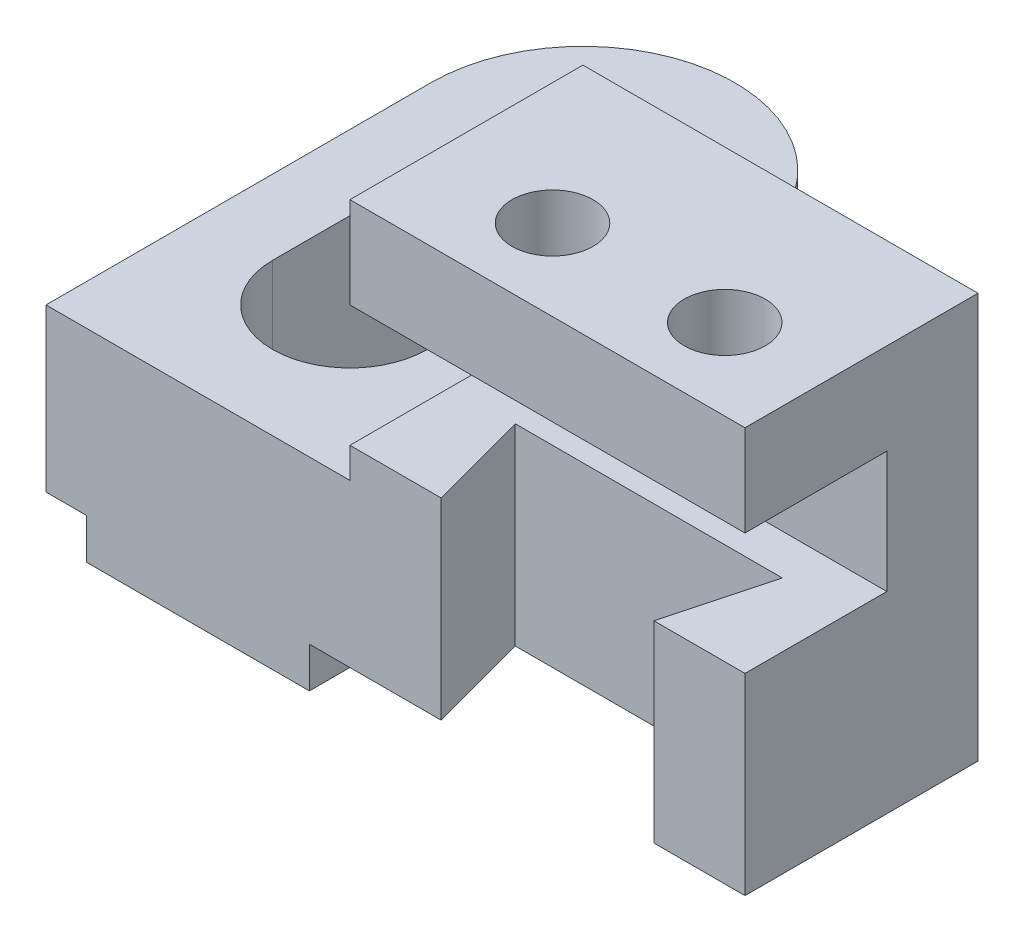
SolidWorks part; units mm, degrees
ref_plane "Front Plane" through (0, 0, 0) normal (0, 0, 1) x (1, 0, 0)
ref_plane "Top Plane" through (0, 0, 0) normal (0, 1, 0) x (1, 0, 0)
ref_plane "Right Plane" through (0, 0, 0) normal (1, 0, 0) x (0, 0, -1)
sketch "Sketch2" plane through (0, 0, 0) normal (0, 1, 0) x (1, 0, 0)
  line L0 (0, 43.411) -> (0, 20.411) construction
  line L1 (-15, 5.411) -> (15, 5.411)
  line L2 (-15, 5.411) -> (-15, 43.411)
  line L3 (-15, 43.411) -> (15, 43.411)
  line L4 (15, 5.411) -> (15, 43.411)
  line L7 (7.6308, 43.411) -> (7.6308, 20.411)
  line L8 (-7.6308, 43.411) -> (-7.6308, 20.411)
  arc A2 (-15, 43.411) -> (15, 43.411) centre (0, 43.411) cw
  arc A3 (7.6308, 43.411) -> (-7.6308, 43.411) centre (0, 43.411) ccw
  arc A4 (-7.6308, 20.411) -> (7.6308, 20.411) centre (0, 20.411) ccw
  point P4 (0, 31.911)
  point P13 (-15, 24.411)
  dimension "D4" = 15
  dimension "D1" = 38
  dimension "D2" = 23
extrude "Boss-Extrude1" add sketch "Sketch2" against normal blind 16 contours A4 L8 L3 L2 L1 L4 L7 | A3 L3 A2
sketch "Sketch4" plane through (15, 0, 0) normal (1, 0, 0) x (0, 0, -1)
  line L1 (5.411, 0) -> (43.411, 0) construction
  line L3 (5.411, 24) -> (5.411, 15)
  line L4 (5.411, 15) -> (19.411, 15)
  line L5 (19.411, 15) -> (19.411, 3)
  line L6 (19.411, 3) -> (5.411, 3)
  line L7 (5.411, 3) -> (5.411, 0)
  line L8 (5.411, -16) -> (5.411, 0) construction
  line L10 (5.411, 24) -> (28.411, 24)
  line L11 (28.411, 24) -> (28.411, 0)
  line L12 (28.411, 0) -> (5.411, 0)
  dimension "D1" = 9
  dimension "D2" = 40
  dimension "D3" = 23
  dimension "D4" = 19
  dimension "D5" = 9
extrude "Boss-Extrude2" add sketch "Sketch4" along normal blind 39 separate body
sketch "Sketch5" plane through (0, 24, 0) normal (0, 1, 0) x (1, 0, 0)
  line L0 (15, 5.411) -> (15, 28.411) construction
  line L1 (54, 5.411) -> (15, 5.411) construction
  circle A0 centre (27, 13.411) radius 4
  circle A1 centre (44, 13.411) radius 4
  dimension "D1" = 8
  dimension "D2" = 8
  dimension "D3" = 12
  dimension "D4" = 17
  dimension "D5" = 8
  dimension "D6" = 8
extrude "Cut-Extrude1" cut sketch "Sketch5" against normal blind 9
sketch "Sketch7" plane through (0, 0, -5.411) normal (0, 0, 1) x (1, 0, 0)
  line L0 (15, 0) -> (54, 0)
  line L1 (54, 0) -> (54, -16)
  line L2 (54, -16) -> (15, -16)
  line L3 (15, -16) -> (15, 0)
extrude "Boss-Extrude3" add sketch "Sketch7" against normal blind 23
sketch "Sketch9" plane through (0, 3, 0) normal (0, 1, 0) x (1, 0, 0)
  line L0 (15, 5.411) -> (24, 5.411)
  line L1 (54, 5.411) -> (15, 5.411) construction
  line L2 (24, 5.411) -> (21.3205, 15.411)
  line L3 (15, 15.411) -> (54, 15.411)
  line L4 (21.3205, 15.411) -> (47.6795, 15.411)
  line L5 (45, 5.411) -> (54, 5.411)
  line L6 (54, 5.411) -> (54, 13.4741)
  line L7 (54, 28.411) -> (54, 5.411) construction
  line L8 (54, 15.411) -> (54, 13.4741)
  line L9 (15, 5.411) -> (15, 28.411) construction
  line L10 (15, 13.4741) -> (15, 5.411)
  line L11 (15, 5.411) -> (24, 5.411)
  line L12 (15, 5.411) -> (54, 5.411)
  line L13 (47.6795, 15.411) -> (45, 5.411)
  line L14 (15, 15.411) -> (15, 13.4741)
  line L15 (24, 5.411) -> (45, 5.411)
  line M6 (15, 5.411) -> (54, 5.411)
  dimension "D1" = 75
  dimension "D2" = 75
  dimension "D3" = 10
  dimension "D4" = 21
extrude "Cut-Extrude2" cut sketch "Sketch9" against normal blind 23 contours L13 L3 L2 M6
sketch "Sketch10" plane through (0, 0, -5.411) normal (0, 0, 1) x (1, 0, 0)
  line L0 (-11, -16) -> (11, -16)
  line L1 (-15, -16) -> (24, -16) construction
  line L2 (11, -16) -> (11, -20)
  line L3 (11, -20) -> (-11, -20)
  line L4 (-11, -20) -> (-11, -16)
  line L5 (-15, -16) -> (-15, 0) construction
  line L7 (24, -16) -> (24, 3) construction
  line L8 (45, -16) -> (45, 3) construction
  dimension "D1" = 4
  dimension "D2" = 22
  dimension "D3" = 4
  dimension "D4" = 21
extrude "Boss-Extrude4" add sketch "Sketch10" against normal blind 5
